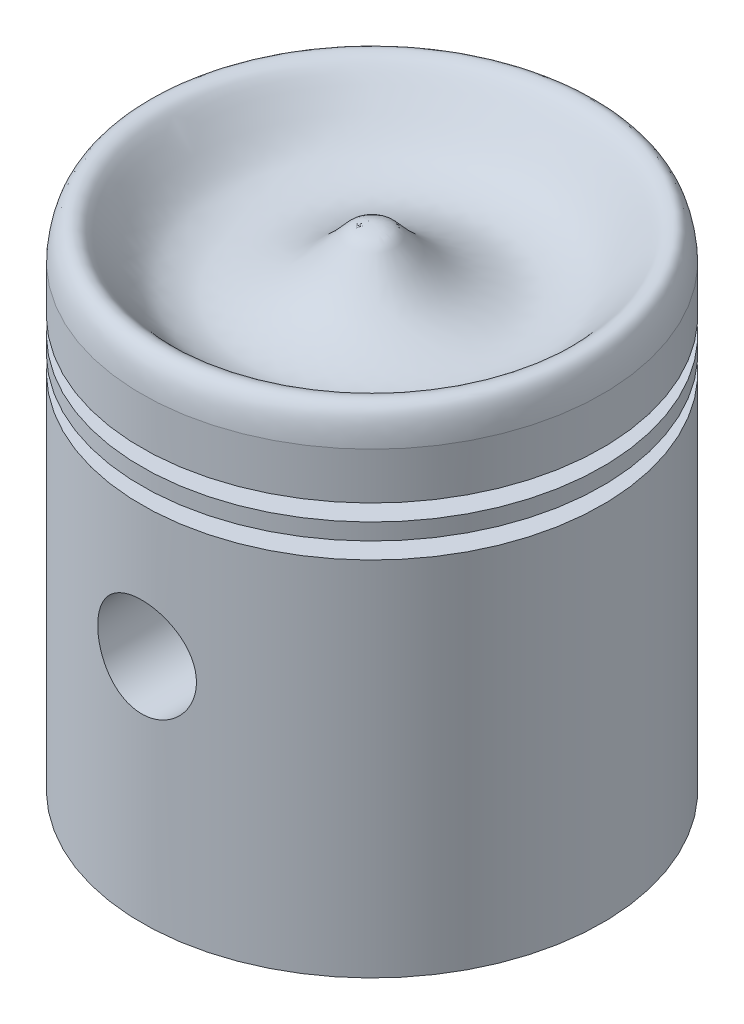
SolidWorks part; units mm, degrees
ref_plane "Ön Düzlem" through (0, 0, 0) normal (0, 0, 1) x (1, 0, 0)
ref_plane "Üst Düzlem" through (0, 0, 0) normal (0, 1, 0) x (1, 0, 0)
ref_plane "Sağ Düzlem" through (0, 0, 0) normal (1, 0, 0) x (0, 0, -1)
sketch "Sketch1" plane through (0, 0, 0) normal (0, 0, 1) x (1, 0, 0)
  line L0 (0, 2.4208) -> (0, -6.1354) construction
  line L4 (-7, 8.7121) -> (-7, 7.2957)
  line L5 (-7, -5.2043) -> (-6.25, -5.2043)
  line L6 (-6.25, -5.2043) -> (-5.0506, -1.9089)
  line L7 (-4.75, -0.2043) -> (-4.75, 4.4401)
  line L9 (0, 8.5662) -> (0, 9.6917)
  line L11 (0, 2.4208) -> (0, 8.5662) construction
  line L12 (-3.4761, 6.2594) -> (0, 7.5246)
  line L13 (0, 7.5246) -> (0, 8.5662)
  line L14 (-7, 5.7957) -> (-7, -5.2043)
  line L15 (-7, 7.2957) -> (-6, 7.2957)
  line L17 (-7, 6.7957) -> (-6, 6.7957)
  line L18 (-6, 7.2957) -> (-6, 6.7957)
  line L19 (-7, 6.2957) -> (-6, 6.2957)
  line L21 (-7, 5.7957) -> (-6, 5.7957)
  line L22 (-6, 6.2957) -> (-6, 5.7957)
  line L23 (-7, 6.7957) -> (-7, 6.2957)
  arc A0 (-3.4761, 6.2594) -> (-4.75, 4.4401) centre (-2.814, 4.4401) ccw
  arc A1 (-4.75, -0.2043) -> (-5.0506, -1.9089) centre (-9.7338, -0.2043) cw
  spline S0 degree 3 poles (-7, 8.7121) (-6.9159, 9.6729) (-6.5719, 9.7865) (-6.0171, 9.562) (-5.1735, 8.3204) (-3.9295, 7.778) (-3.2579, 7.7706) (-1.6216, 8.3745) (-0.9881, 9.0782) (-0.5143, 9.6341) (-0.1875, 9.6953) (0, 9.6917) knots 0 0 0 0 0.210747 0.254088 0.413487 0.459298 0.666392 0.71499 0.89668 0.927453 1 1 1 1
  point P5 (-2.375, 8.1)
  point P11 (-4.75, -0.2043)
  point P22 (-4.6517, 8.1)
  point P25 (-3.4761, 6.2594)
  point P26 (-4.75, 4.4401)
  point P30 (-5.0506, -1.9089)
  dimension "D10" = 4.6444
  dimension "D11" = 3.4761
  dimension "D1" = 7
  dimension "D2" = 0.5
  dimension "D3" = 1
  dimension "D4" = 12.5
  dimension "D5" = 6.25
  dimension "D6" = 5
  dimension "D7" = 20
  dimension "D8" = 3.2954
  dimension "D9" = 70
revolve "Revolve1" add sketch "Sketch1" angle 360 about L11
sketch "Sketch2" plane through (0, 0, 0) normal (0, 0, 1) x (1, 0, 0)
  line L0 (-7, -5.2043) -> (7, -5.2043) construction
  circle A0 centre (0, 1.7957) radius 1.5
  dimension "D1" = 7
extrude "Cut-Extrude1" cut sketch "Sketch2" against normal through all both and the other way through all
scale "Scale1" scale about centroid uniform scaling yes scale factor 1.5
